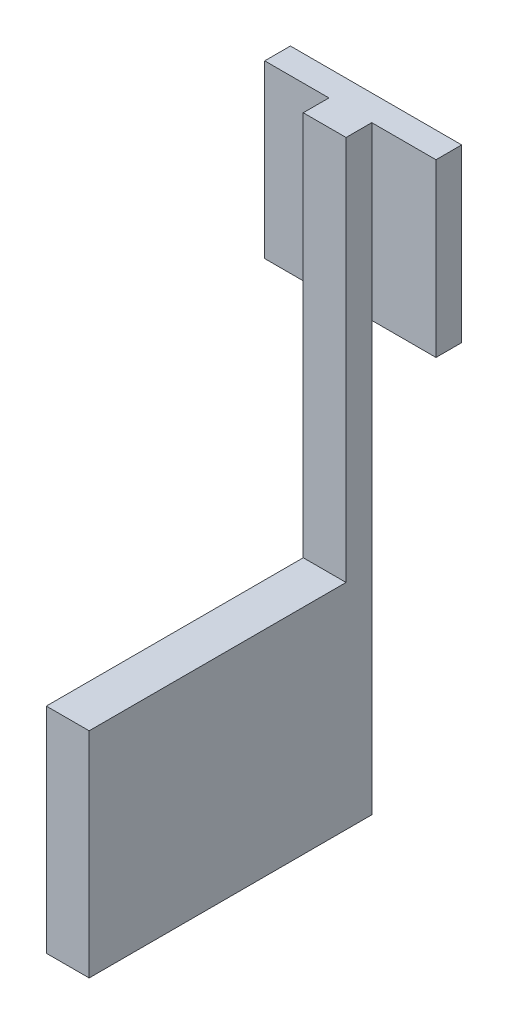
SolidWorks part; units mm, degrees
ref_plane "前视基准面" through (0, 0, 0) normal (0, 0, 1) x (1, 0, 0)
ref_plane "上视基准面" through (0, 0, 0) normal (0, 1, 0) x (1, 0, 0)
ref_plane "右视基准面" through (0, 0, 0) normal (1, 0, 0) x (0, 0, -1)
sketch "草图1" plane through (0, 0, 0) normal (0, 0, 1) x (1, 0, 0)
  line L1 (-10, -10) -> (10, -10)
  line L2 (-10, -10) -> (-10, 10)
  line L3 (-10, 10) -> (10, 10)
  line L4 (10, -10) -> (10, 10)
  line L5 (-10, -10) -> (10, 10) construction
  line L6 (-10, 10) -> (10, -10) construction
  point P0 (0, 0)
  dimension "D1" = 20
  dimension "D2" = 20
extrude "凸台-拉伸1" add sketch "草图1" along normal blind 3
sketch "草图2" plane through (0, 0, 3) normal (0, 0, 1) x (1, 0, 0)
  line L0 (10, 10) -> (-10, 10) construction
  line L1 (-2.5, -10) -> (2.5, -10)
  line L2 (-2.5, -10) -> (-2.5, 10)
  line L3 (-2.5, 10) -> (2.5, 10)
  line L4 (2.5, -10) -> (2.5, 10)
  line L5 (-2.5, -10) -> (2.5, 10) construction
  line L6 (-2.5, 10) -> (2.5, -10) construction
  point P0 (0, 0)
  dimension "D1" = 5
extrude "凸台-拉伸2" add sketch "草图2" along normal blind 3
sketch "草图3" plane through (0, -10, 0) normal (0, -1, 0) x (1, 0, 0)
  line L1 (-2.5, 6) -> (2.5, 6)
  line L2 (-2.5, 6) -> (-2.5, 3)
  line L3 (-2.5, 3) -> (2.5, 3)
  line L4 (2.5, 6) -> (2.5, 3)
extrude "凸台-拉伸3" add sketch "草图3" along normal blind 50
sketch "草图4" plane through (0, 0, 6) normal (0, 0, 1) x (1, 0, 0)
  line L0 (-2.5, 10) -> (-2.5, -60) construction
  line L1 (2.5, -60) -> (-2.5, -60)
  line L2 (2.5, -60) -> (2.5, -35)
  line L3 (2.5, -35) -> (-2.5, -35)
  line L4 (-2.5, -60) -> (-2.5, -35)
  dimension "D1" = 25
extrude "凸台-拉伸4" add sketch "草图4" along normal blind 30
